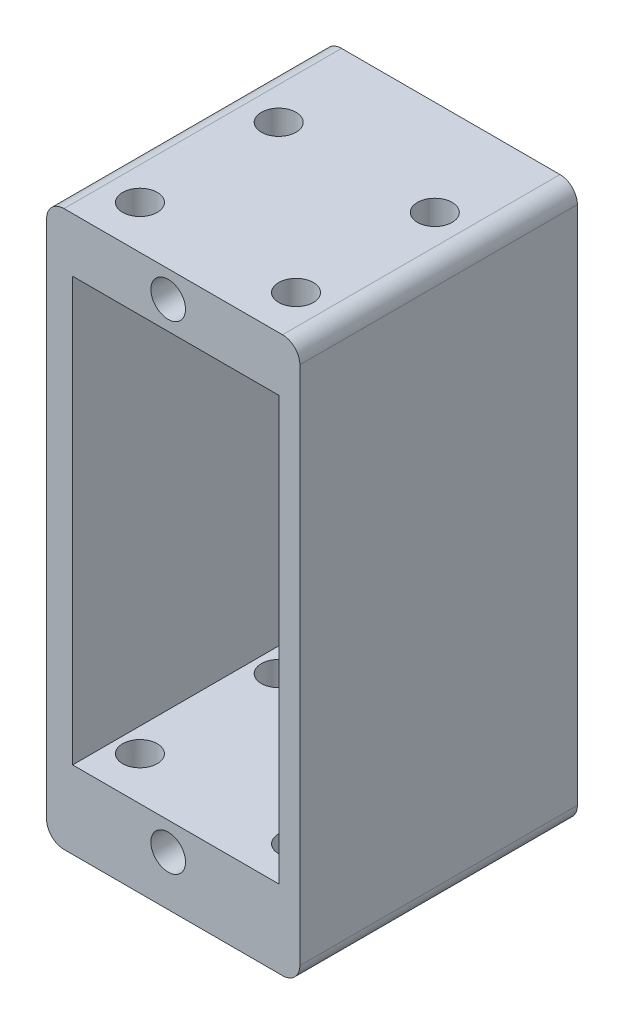
SolidWorks part; units mm, degrees
ref_plane "Front Plane" through (0, 0, 0) normal (0, 0, 1) x (1, 0, 0)
ref_plane "Top Plane" through (0, 0, 0) normal (0, 1, 0) x (1, 0, 0)
ref_plane "Right Plane" through (0, 0, 0) normal (1, 0, 0) x (0, 0, -1)
other "Graphic1"
other "object_1 (Open) -1"
sketch "Sketch2" plane through (0, 0, 0) normal (0, 0, 1) x (1, 0, 0)
  line L1 (-106.7177, 235.3278) -> (-92.1177, 235.3278)
  line L2 (-106.7177, 235.3278) -> (-106.7177, 203.3278)
  line L3 (-106.7177, 203.3278) -> (-92.1177, 203.3278)
  line L4 (-92.1177, 235.3278) -> (-92.1177, 203.3278)
  dimension "D1" = 14.6
  dimension "D2" = 32
extrude "Boss-Extrude1" add sketch "Sketch2" along normal blind 16
fillet "Fillet1" radius 1 4 edges at (-92.1177, 203.3278, 8) (-106.7177, 203.3278, 8) (-92.1177, 235.3278, 8) (-106.7177, 235.3278, 8)
sketch "Sketch3" plane through (0, 0, 16) normal (0, 0, 1) x (1, 0, 0)
  line L0 (-92.1177, 204.3278) -> (-92.1177, 234.3278) construction
  line L3 (-105.2177, 232.2) -> (-93.3177, 232.2)
  line L4 (-105.2177, 232.2) -> (-105.2177, 207.8)
  line L5 (-105.2177, 207.8) -> (-93.3177, 207.8)
  line L6 (-93.3177, 232.2) -> (-93.3177, 207.8)
  dimension "D1" = 11.9
  dimension "D2" = 24.4
  dimension "D3" = 1.2
extrude "Cut-Extrude1" cut sketch "Sketch3" against normal blind 16
sketch "Sketch4" plane through (0, 0, 16) normal (0, 0, 1) x (1, 0, 0)
  line L0 (-93.3177, 232.2) -> (-105.2177, 232.2) construction
  line L1 (-105.2177, 207.8) -> (-93.3177, 207.8) construction
  circle A0 centre (-99.7091, 233.8) radius 1
  circle A1 centre (-99.7091, 206.2) radius 1
  dimension "D1" = 1.6
  dimension "D2" = 1.6
extrude "Cut-Extrude2" cut sketch "Sketch4" against normal blind 16
sketch "Sketch5" plane through (0, 235.3278, 0) normal (0, 1, 0) x (1, 0, 0)
  line L0 (-123.5056, -5.5) -> (-84.1695, -5.5) construction
  line L1 (-103.8376, -5.5) -> (-103.8376, -13.5) construction
  circle A0 centre (-103.8376, -5.5) radius 1
  circle A1 centre (-94.8376, -5.5) radius 1
  circle A2 centre (-94.8376, -13.5) radius 1
  circle A3 centre (-103.8376, -13.5) radius 1
  dimension "D1" = 2
  dimension "D3" = 8
  dimension "D2" = 2
extrude "Cut-Extrude3" cut sketch "Sketch5" against normal through all
